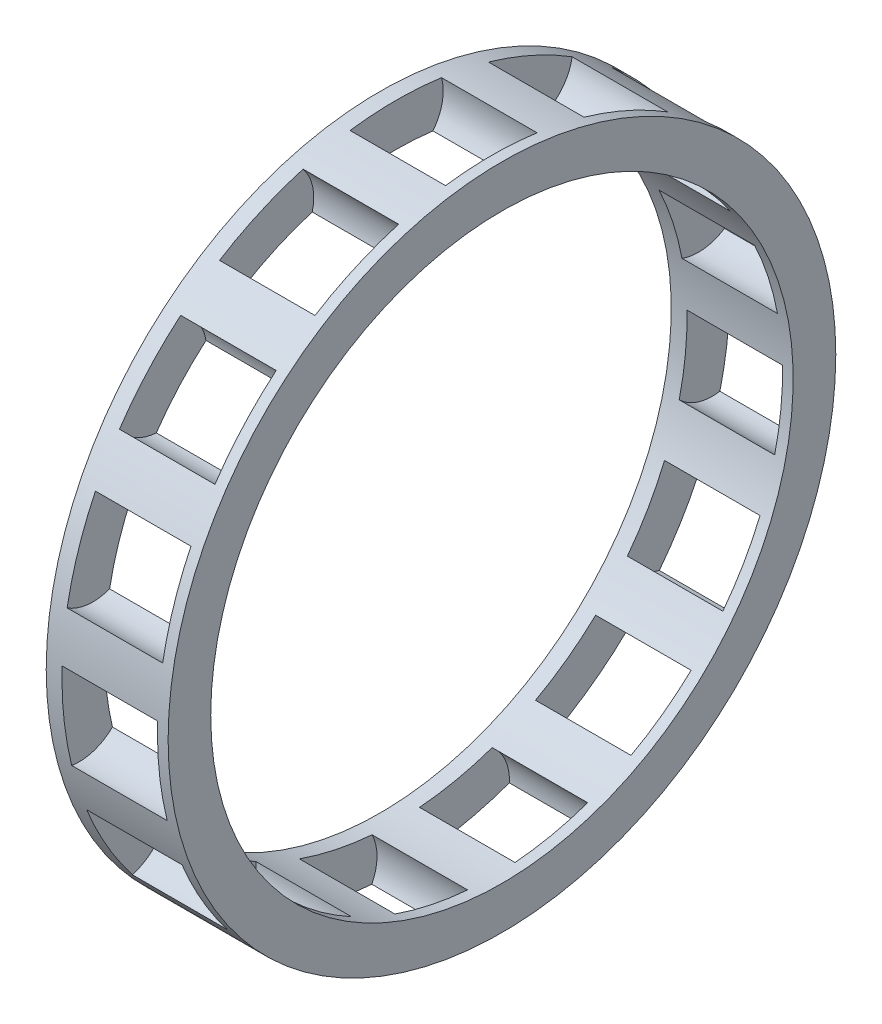
SolidWorks part; units mm, degrees
ref_plane "Plan1" through (0, 0, 0) normal (0, 0, 1) x (1, 0, 0)
ref_plane "Plan2" through (0, 0, 0) normal (0, 1, 0) x (1, 0, 0)
ref_plane "Plan3" through (0, 0, 0) normal (1, 0, 0) x (0, 0, -1)
sketch "Esquisse1" plane through (0, 0, 0) normal (0, 0, 1) x (1, 0, 0)
  line L0 (-5.6394, 21.5) -> (3.3606, 21.5)
  line L1 (-5.6394, 21.5) -> (-5.6394, 24.6466)
  line L2 (-5.6394, 24.6466) -> (3.3606, 24.6466)
  line L3 (3.3606, 24.6466) -> (3.3606, 21.5)
  line L4 (-8.7711, 0) -> (4.2031, 0) construction
  line L5 (43.7916, 0) -> (-206.2084, 0) construction
revolve "Base-Révolution" add sketch "Esquisse1" angle 360 about L4
sketch "Esquisse2" plane through (0, 0, 0) normal (0, 0, 1) x (1, 0, 0)
  line L0 (-7.6974, 23.5) -> (4.0242, 23.5) construction
  line L1 (-4.4762, 27) -> (-4.4762, 23.5)
  line L3 (-4.4762, 27) -> (-4.4762, 20) construction
  line L4 (-4.4762, 27) -> (2.5738, 27)
  line L6 (2.5238, 27) -> (-4.4762, 27) construction
  line L7 (2.5738, 27) -> (2.5738, 23.5)
  line L8 (2.5738, 23.5) -> (-4.4762, 23.5)
revolve "Enlèvement de matière-Révolution1" cut sketch "Esquisse2" angle 360 about L0
pattern_circular "Répétition circulaire1" count 15 every 24
